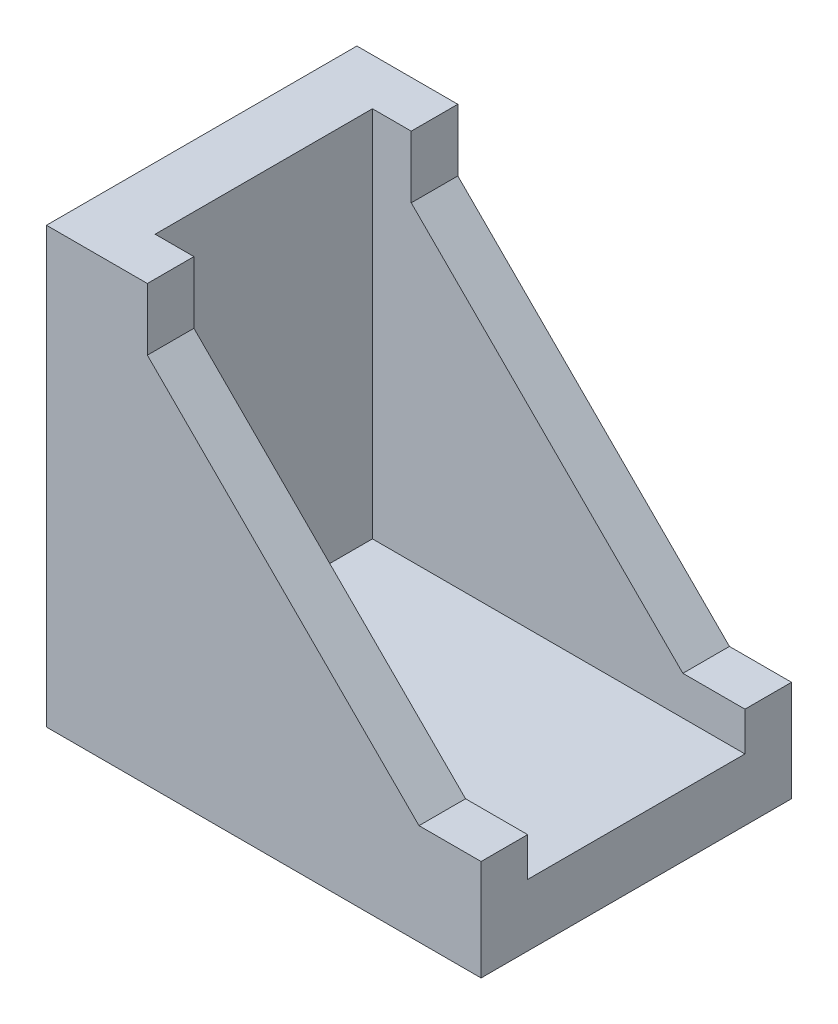
SolidWorks part; units mm, degrees
material "1060 合金"
ref_plane "前视基准面" through (0, 0, 0) normal (0, 0, 1) x (1, 0, 0)
ref_plane "上视基准面" through (0, 0, 0) normal (0, 1, 0) x (1, 0, 0)
ref_plane "右视基准面" through (0, 0, 0) normal (1, 0, 0) x (0, 0, -1)
other "Configuration Table"
sketch "草图1" plane through (0, 0, 0) normal (0, 0, 1) x (1, 0, 0)
  line L0 (14, -7.5) -> (10, -7.5)
  line L1 (-14, 14) -> (-7.5, 14)
  line L2 (-14, 14) -> (-14, -14)
  line L3 (-14, -14) -> (14, -14)
  line L4 (14, -7.5) -> (14, -14)
  line L7 (-7.5, 14) -> (-7.5, 10)
  line L8 (-7.5, 10) -> (10, -7.5)
  point P0 (0, 0)
  dimension "D1" = 28
  dimension "D2" = 28
  dimension "D3" = 6.5
  dimension "D4" = 6.5
  dimension "D5" = 4
  dimension "D6" = 4
  dimension "D7" = 14
  dimension "D8" = 14
extrude "凸台-拉伸1" add sketch "草图1" along normal blind 20
sketch "草图2" plane through (0, 0, 0) normal (0, 0, 1) x (1, 0, 0)
  line L0 (-14, 14) -> (-14, -14) construction
  line L1 (-10, -10) -> (15.6383, -10)
  line L2 (-10, -10) -> (-10, 15.0269)
  line L3 (-10, 15.0269) -> (15.6383, 15.0269)
  line L4 (15.6383, -10) -> (15.6383, 15.0269)
  line L6 (-14, -14) -> (14, -14) construction
  dimension "D1" = 4
  dimension "D2" = 4
extrude "切除-拉伸1" cut sketch "草图2" along normal offset from surface (14 mm away) 3 from offset 3 up to face at (-0.7143, -0.7143, 20)
